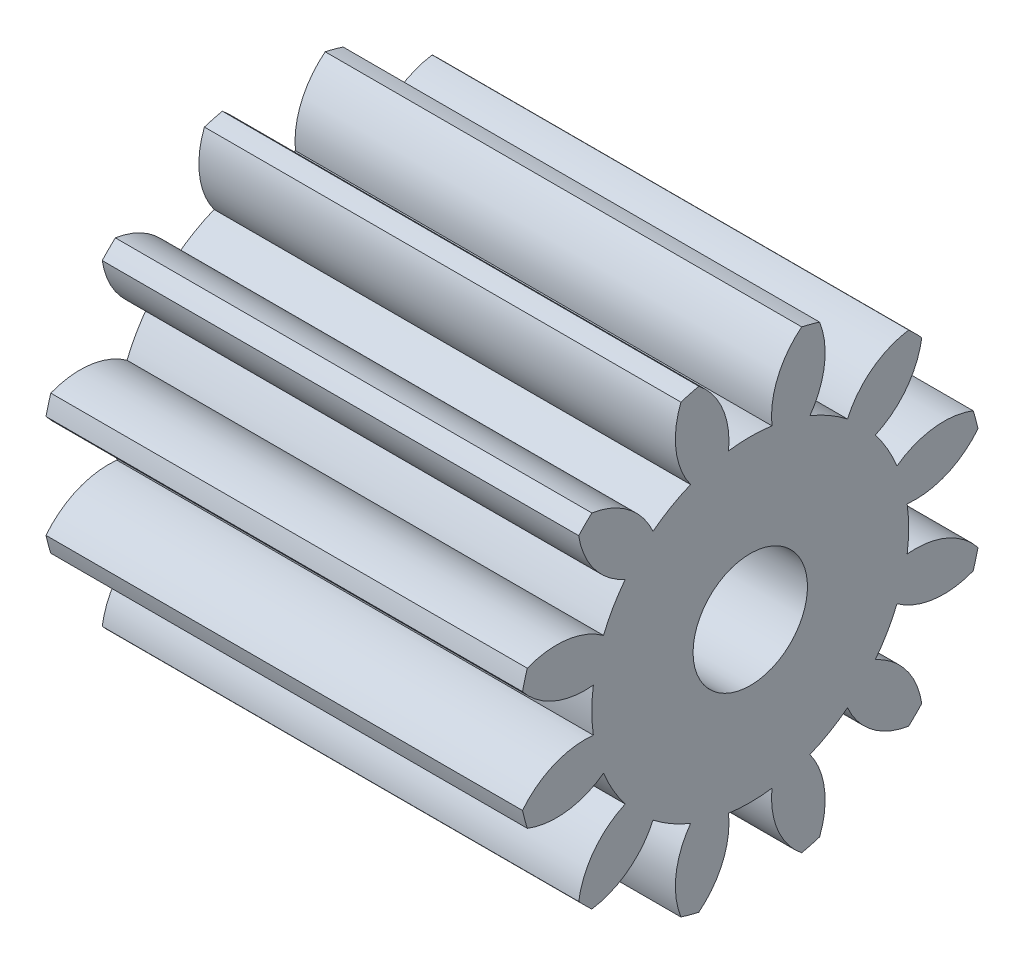
SolidWorks part; units mm, degrees
ref_plane "Plane1" through (0, 0, 0) normal (0, 0, 1) x (1, 0, 0)
ref_plane "Plane2" through (0, 0, 0) normal (0, 1, 0) x (1, 0, 0)
ref_plane "Plane3" through (0, 0, 0) normal (1, 0, 0) x (0, 0, -1)
sketch "HoldingSke" plane through (0, 0, 0) normal (0, 1, 0) x (1, 0, 0)
  line L0 (0, 0) -> (1.3974, -0.297)
  line L1 (-15, 0) -> (100, 0) construction
  line L2 (0, 0) -> (-2.1039, 2.3779)
  line L3 (0, 0) -> (-11.863, 4.5341)
  line L4 (0, 0) -> (8.4473, 1.7955)
  line L5 (0, 0) -> (-46.8476, -17.4728)
  line L6 (0, 0) -> (-8.2896, -5.593)
  line L7 (-2.1039, 2.3779) -> (8.6586, 51.2059)
  line L8 (-76.2, 54.61) -> (-76.1, 54.61)
  line L9 (-67.7845, 28.3722) -> (-49.3413, 33.142)
  line L10 (-76.2, 71.12) -> (104.1128, 71.12)
  line L11 (0, 0) -> (-10, 0)
  line L12 (-76.2, 101.6) -> (-76.173, 101.6)
  line L13 (24.9733, 27.94) -> (52.9518, 28.4284)
  line L14 (24.9733, 27.94) -> (24.9743, 27.94)
  line L15 (24.9733, 27.94) -> (100.4006, 29.5858)
  line L16 (-63.627, -0.7) -> (-12.827, -0.7)
  circle A0 centre (0, 0) radius 0.5
  circle A1 centre (0, 0) radius 3.324
  circle A2 centre (0, 0) radius 37.5
  circle A3 centre (0, 0) radius 0.5
  dimension "MHD" = 6.648
  dimension "Hub_dia" = 75
  dimension "Bore" = 1
  dimension "MBD" = 1
  dimension "Num_teeth" = 12
  dimension "Pitch" = 1.4286
  dimension "Overall_len" = 50
  dimension "Show_teeth" = 12
  dimension "Thickness" = 10
  dimension "OAL" = 50.0001
  dimension "T_dim" = 0.1
  dimension "Ap" = 14.5
  dimension "H" = 19.05
  dimension "Pitch_radius" = 180.3128
  dimension "Width" = 10
  dimension "Backlash" = 0.027
  dimension "Addendum_fac" = 1
  dimension "Dedendum_fac" = 1.25
  dimension "Clearance_fac" = 0.25
  dimension "Dedendum_add" = 0.001
  dimension "Module" = 0.7
sketch "BasProSke" plane through (0, 0, 0) normal (0, 1, 0) x (1, 0, 0)
  line L0 (-10, 0) -> (60, 0) construction
  line L1 (0, 0) -> (0, 4.9)
  line L2 (0, 0) -> (10, 0)
  line L3 (10, 0) -> (10, 4.9)
  line L4 (10, 4.9) -> (0, 4.9)
  dimension "Thickness" = 10
  dimension "Diameter" = 9.8
revolve "Base-Revolve" add sketch "BasProSke" angle 360 about L0
sketch "TooCutSke" plane through (0, 0, 0) normal (1, 0, 0) x (0, 0, -1)
  line L1 (0, 0) -> (0, 107) construction
  line L2 (0, 0) -> (-0.5954, 4.1576) construction
  line L3 (0, 0) -> (-2.1586, 8.0559) construction
  line L4 (-0.5954, 4.1576) -> (-1.0793, 4.0279) construction
  arc A0 (0.4554, 3.2927) -> (-0.4554, 3.2927) centre (0, 0) ccw
  arc A1 (1.1051, 4.7998) -> (-1.1051, 4.7998) centre (0, 0) ccw
  circle A2 centre (0, 0) radius 4.2 construction
  circle A3 centre (0, 0) radius 4.0662 construction
  arc A4 (-0.4554, 3.2927) -> (-1.1051, 4.7998) centre (-2.1264, 3.4659) ccw
  arc A5 (1.1051, 4.7998) -> (0.4554, 3.2927) centre (2.1264, 3.4659) ccw
  dimension "Root_dia" = 6.648
  dimension "Overcut_dia" = 9.8508
  dimension "Pitch_dia" = 8.4
  dimension "Base_dia" = 8.1324
  dimension "Flank_rad" = 1.68
  dimension "Half_ang" = 15
  dimension "Half_CT" = 0.501
extrude "ToothCut" cut sketch "TooCutSke" along normal through all
fillet "Breaks" [suppressed] radius 0.014
fillet "RootFillets" [suppressed] radius 0.176
pattern_circular "TeethCuts" count 12 every 30 about axis through (-10, 0, 0) along (1, 0, 0) of "ToothCut", "RootFillets", "Breaks"
sketch "HubNeaOneSke" plane through (0, 0, 0) normal (-1, 0, 0) x (0, 0, 1)
  circle A0 centre (0, 0) radius 3.324
  dimension "Diameter" = 6.648
extrude "HubNearOne" [suppressed] add sketch "HubNeaOneSke" along normal blind 40.0001
sketch "HubNeaBotSke" plane through (0, 0, 0) normal (-1, 0, 0) x (0, 0, 1)
  circle A0 centre (0, 0) radius 3.324
  dimension "Diameter" = 6.648
extrude "HubNearBoth" [suppressed] add sketch "HubNeaBotSke" along normal blind 20
ref_plane "FarPln" through (10, 0, 0) normal (1, 0, 0) x (0, 0, -1)
sketch "HubFarSke" plane through (10, 0, 0) normal (1, 0, 0) x (0, 0, -1)
  circle A0 centre (0, 0) radius 3.324
  dimension "Diameter" = 6.648
extrude "HubFar" [suppressed] add sketch "HubFarSke" along normal blind 20
sketch "BorSke" plane through (0, 0, 0) normal (1, 0, 0) x (0, 0, -1)
  circle A0 centre (0, 0) radius 0.5
  dimension "Diameter" = 1
extrude "Bore" cut sketch "BorSke" along normal mid plane 100.0001
sketch "KeySke" plane through (0, 0, 0) normal (1, 0, 0) x (0, 0, -1)
  line L0 (-0.05, 0) -> (-0.05, 0.6)
  line L1 (-0.05, 0.6) -> (0.05, 0.6)
  line L2 (0.05, 0.6) -> (0.05, 0)
  line L3 (0, 0) -> (0, 34) construction
  line L4 (-0.05, 0) -> (0.05, 0)
  dimension "Offset" = 0.6
  dimension "Width" = 0.1
extrude "Keyway" [suppressed] cut sketch "KeySke" along normal mid plane 100.0001
pattern_circular "Keyway2" [suppressed] count 2 every 90 about axis through (-10, 0, 0) along (1, 0, 0)
sketch "Sketch2" plane through (0, 0, 0) normal (-1, 0, 0) x (0, 0, 1)
  circle A0 centre (0, 0) radius 1
  dimension "D1" = 2
extrude "Cut-Extrude1" cut sketch "Sketch2" against normal through all
hole_wizard "CSK for M2 Flat Head Machine Screw1" positions "Sketch3" profile "Sketch4" countersink size "M2" standard "ANSI Metric" end condition through all
sketch "Sketch3" plane through (0, 0, 0) normal (-1, 0, 0) x (0, 0, 1)
  point P0 (0, 0)
sketch "Sketch4" plane through (0, 0, 0) normal (0, 1, 0) x (0, 0, 1)
  line L0 (0, 0) -> (0, 10)
  line L1 (0, 10) -> (1.2, 10)
  line L2 (1.2, 10) -> (1.2, 1)
  line L3 (1.2, 1) -> (2.2, 0)
  line L5 (2.2, 0) -> (0, 0)
  line L6 (-1.2, 1) -> (-2.2, 0) construction
  line L11 (0, -6.35) -> (0, 107.95) construction
  dimension "Thru Hole Dia." = 2.4
  dimension "Thru Hole Depth" = 10
  dimension "Near C'Sink Dia." = 4.4
  dimension "Near C'Sink Angle" = 90
equation "' \"Module@HoldingSke\" = 6.35"
equation "' \"Num_teeth@HoldingSke\" = 12"
equation "' \"Ap@HoldingSke\" =  20"
equation "' \"Ap@HoldingSke\" = 20"
equation "' \"Width@HoldingSke\" = 0.5 * 25.4"
equation "' \"Hub_dia@HoldingSke\"= 1 * 25.4"
equation "' \"Hub_dia@HoldingSke\" = 1 * 25.4"
equation "' \"Overall_len@HoldingSke\" = 1.0 * 25.4"
equation "' \"Bore@HoldingSke\" = 0.75 * 25.4"
equation "' \"T_dim@HoldingSke\" = 0.1 * 25.4"
equation "' \"Width@KeySke\" = 0.25 * 25.4"
equation "' \"Show_teeth@HoldingSke\" = 13"
equation "' \"Backlash@HoldingSke\" = 0.009 * 25.4"
equation "' \"Addendum_fac@HoldingSke\" = 1.0"
equation "' \"Dedendum_fac@HoldingSke\" = 1.25"
equation "' \"Dedendum_add@HoldingSke\" = 0.00005 * 25.4"
equation "' \"Clearance_fac@HoldingSke\" = 0.25"
equation "\"Pitch@HoldingSke\" = 1 / \"Module@HoldingSke\""
equation "\"Overcut_dia@TooCutSke\" = (\"Num_teeth@HoldingSke\" + 2 * \"Addendum_fac@HoldingSke\") / \"Pitch@HoldingSke\" + 0.002 * 25.4"
equation "\"Pitch_dia@TooCutSke\" = \"Num_teeth@HoldingSke\" / \"Pitch@HoldingSke\""
equation "\"Base_dia@TooCutSke\" = \"Num_teeth@HoldingSke\" / \"Pitch@HoldingSke\" * cos((\"Ap@HoldingSke\"  * 3.14159265 / 180))"
equation "\"Root_dia@TooCutSke\" = (\"Num_teeth@HoldingSke\" + 2) / \"Pitch@HoldingSke\" - 2 * (\"Addendum_fac@HoldingSke\" + \"Dedendum_fac@HoldingSke\") / \"Pitch@HoldingSke\" - \"Dedendum_add@HoldingSke\" * 2"
equation "\"Half_ang@TooCutSke\" = 180 / \"Num_teeth@HoldingSke\""
equation "\"Half_CT@TooCutSke\" = \"Num_teeth@HoldingSke\" / \"Pitch@HoldingSke\" * sin((3.14159265 / 2 / \"Num_teeth@HoldingSke\")) / 2 - 7 * \"Backlash@HoldingSke\" / 4"
equation "\"Flank_rad@TooCutSke\" = \"Num_teeth@HoldingSke\" / \"Pitch@HoldingSke\" / 5"
equation "\"Radius@RootFillets\" = \"Clearance_fac@HoldingSke\" / \"Pitch@HoldingSke\" + \"Dedendum_add@HoldingSke\""
equation "\"Break_rad@Breaks\" = 0.02 / \"Pitch@HoldingSke\""
equation "\"Thickness@HoldingSke\" = \"Width@HoldingSke\""
equation "\"OAL@HoldingSke\" = \"Thickness@HoldingSke\""
equation "\"MHD@HoldingSke\" = (\"Num_teeth@HoldingSke\" + 2) / \"Pitch@HoldingSke\" - 2 * (\"Addendum_fac@HoldingSke\" + \"Dedendum_fac@HoldingSke\")  / \"Pitch@HoldingSke\" - \"Dedendum_add@HoldingSke\" * 2"
equation "\"MBD@HoldingSke\" = (\"Num_teeth@HoldingSke\" + 2) / \"Pitch@HoldingSke\" - 2 * (\"Addendum_fac@HoldingSke\" + \"Dedendum_fac@HoldingSke\")  / \"Pitch@HoldingSke\" - \"Dedendum_add@HoldingSke\" * 2 - 0.002 * 25.4"
equation "\"MHD@HoldingSke\" = ((sgn( \"MHD@HoldingSke\" - \"Hub_dia@HoldingSke\" )-1)*( \"MHD@HoldingSke\" - \"Hub_dia@HoldingSke\" ))/-2+ \"Hub_dia@HoldingSke\""
equation "\"MBD@HoldingSke\" = ((sgn( \"MBD@HoldingSke\" - \"Bore@HoldingSke\" )-1)*( \"MBD@HoldingSke\" - \"Bore@HoldingSke\" ))/-2+ \"Bore@HoldingSke\""
equation "\"OAL@HoldingSke\" = ((sgn( \"OAL@HoldingSke\" - \"Overall_len@HoldingSke\" )+1)*( \"OAL@HoldingSke\" - \"Overall_len@HoldingSke\" ))/2 + \"Overall_len@HoldingSke\" + 0.000002 * 25.4"
equation "\"Num_teeth@TeethCuts\" = int( \"Show_teeth@HoldingSke\" ) + 1"
equation "\"Num_teeth@TeethCuts\" = ((sgn( \"Num_teeth@TeethCuts\" - \"Num_teeth@HoldingSke\" )-1)*( \"Num_teeth@TeethCuts\" - \"Num_teeth@HoldingSke\" ))/-2+ \"Num_teeth@HoldingSke\""
equation "\"Num_teeth@TeethCuts\" = ((sgn( \"Num_teeth@TeethCuts\" - 2.0)+1)*( \"Num_teeth@TeethCuts\" - 2.0))/2 +2.0"
equation "\"Angle@TeethCuts\" = 360.0 / \"Num_teeth@HoldingSke\""
equation "\"Diameter@BasProSke\" = (\"Num_teeth@HoldingSke\" + 2 * \"Addendum_fac@HoldingSke\") / \"Pitch@HoldingSke\""
equation "\"Thickness@BasProSke\"  = \"Thickness@HoldingSke\""
equation "' \"Fillet_rad@BasProSke\" =  \"Thickness@HoldingSke\" * 0.05"
equation "' \"Fillet_rad@BasProSke\" = \"Thickness@HoldingSke\" * 0.05"
equation "\"MHD@HoldingSke\" = ((sgn( \"MHD@HoldingSke\" - \"Root_dia@TooCutSke\" )-1)*( \"MHD@HoldingSke\" - \"Root_dia@TooCutSke\" ))/-2+ \"Root_dia@TooCutSke\""
equation "\"Diameter@HubNeaOneSke\" = \"MHD@HoldingSke\""
equation "\"Length@HubNearOne\" = \"OAL@HoldingSke\" - \"Thickness@BasProSke\""
equation "\"Diameter@HubNeaBotSke\" = \"MHD@HoldingSke\""
equation "\"Length@HubNearBoth\" = ( \"OAL@HoldingSke\" - \"Thickness@BasProSke\" ) / 2.0"
equation "\"Thickness@FarPln\" = \"Thickness@BasProSke\""
equation "\"Diameter@HubFarSke\" = \"MHD@HoldingSke\""
equation "\"Length@HubFar\" = ( \"OAL@HoldingSke\" - \"Thickness@BasProSke\" ) / 2.0"
equation "\"Diameter@BorSke\" = \"MBD@HoldingSke\""
equation "\"D1@Bore\" = \"OAL@HoldingSke\" * 2.0"
equation "\"D1@Keyway\" = \"OAL@HoldingSke\" * 2.0"
equation "\"Offset@KeySke\" = \"T_dim@HoldingSke\" + \"MBD@HoldingSke\" / 2.0"
